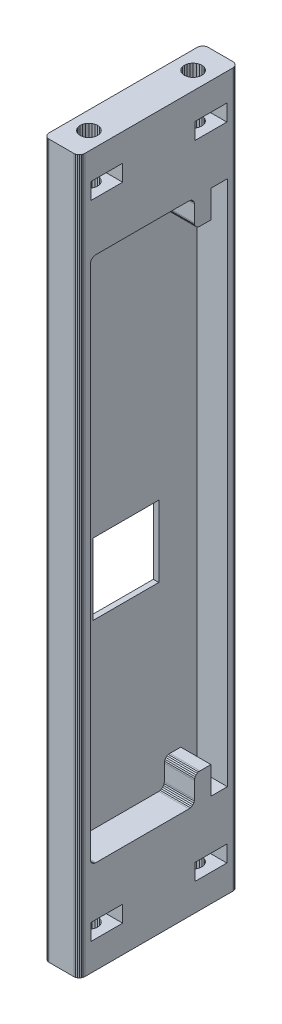
SolidWorks part; units mm, degrees
ref_plane "Front Plane" through (0, 0, 0) normal (0, 0, 1) x (1, 0, 0)
ref_plane "Top Plane" through (0, 0, 0) normal (0, 1, 0) x (1, 0, 0)
ref_plane "Right Plane" through (0, 0, 0) normal (1, 0, 0) x (0, 0, -1)
ref_plane "Plane1" through (0, 130, 0) normal (0, 1, 0) x (1, 0, 0)
sketch "Sketch1" plane through (0, 130, 0) normal (0, 1, 0) x (1, 0, 0)
  line L0 (3.2159, -23.2588) -> (3.25, -23)
  line L1 (3.25, -23) -> (3.25, 4)
  line L2 (3.25, 4) -> (3.2159, 4.2588)
  line L3 (3.2159, 4.2588) -> (3.116, 4.5)
  line L4 (3.116, 4.5) -> (2.9571, 4.7071)
  line L5 (2.9571, 4.7071) -> (2.75, 4.866)
  line L6 (2.75, 4.866) -> (2.5088, 4.9659)
  line L7 (2.5088, 4.9659) -> (2.25, 5)
  line L8 (2.25, 5) -> (-2.25, 5)
  line L9 (-2.25, 5) -> (-2.5088, 4.9659)
  line L10 (-2.5088, 4.9659) -> (-2.75, 4.866)
  line L11 (-2.75, 4.866) -> (-2.9571, 4.7071)
  line L12 (-2.9571, 4.7071) -> (-3.116, 4.5)
  line L13 (-3.116, 4.5) -> (-3.2159, 4.2588)
  line L14 (-3.2159, 4.2588) -> (-3.25, 4)
  line L15 (-3.25, 4) -> (-3.25, -23)
  line L16 (-3.25, -23) -> (-3.2159, -23.2588)
  line L17 (-3.2159, -23.2588) -> (-3.116, -23.5)
  line L18 (-3.116, -23.5) -> (-2.9571, -23.7071)
  line L19 (-2.9571, -23.7071) -> (-2.75, -23.866)
  line L20 (-2.75, -23.866) -> (-2.5088, -23.9659)
  line L21 (-2.5088, -23.9659) -> (-2.25, -24)
  line L22 (-2.25, -24) -> (2.25, -24)
  line L23 (2.25, -24) -> (2.5088, -23.9659)
  line L24 (2.5088, -23.9659) -> (2.75, -23.866)
  line L25 (2.75, -23.866) -> (2.9571, -23.7071)
  line L26 (2.9571, -23.7071) -> (3.116, -23.5)
  line L27 (3.116, -23.5) -> (3.2159, -23.2588)
extrude "Boss-Extrude1" add sketch "Sketch1" against normal blind 130
sketch "Sketch2" plane through (-3.25, 0, 0) normal (-1, 0, 0) x (0, 0, 1)
  line L0 (16.1, 5) -> (21.9, 5)
  line L1 (21.9, 5) -> (21.9, 8)
  line L2 (21.9, 8) -> (16.1, 8)
  line L3 (16.1, 8) -> (16.1, 5)
extrude "Cut-Extrude1" cut sketch "Sketch2" against normal through all
sketch "Sketch3" plane through (0, 0, 0) normal (0, -1, 0) x (1, 0, 0)
  line L0 (1.5455, 18.5859) -> (1.6, 19)
  line L1 (1.6, 19) -> (1.5455, 19.4141)
  line L2 (1.5455, 19.4141) -> (1.3856, 19.8)
  line L3 (1.3856, 19.8) -> (1.1314, 20.1314)
  line L4 (1.1314, 20.1314) -> (0.8, 20.3856)
  line L5 (0.8, 20.3856) -> (0.4141, 20.5455)
  line L6 (0.4141, 20.5455) -> (0, 20.6)
  line L7 (0, 20.6) -> (-0.4141, 20.5455)
  line L8 (-0.4141, 20.5455) -> (-0.8, 20.3856)
  line L9 (-0.8, 20.3856) -> (-1.1314, 20.1314)
  line L10 (-1.1314, 20.1314) -> (-1.3856, 19.8)
  line L11 (-1.3856, 19.8) -> (-1.5455, 19.4141)
  line L12 (-1.5455, 19.4141) -> (-1.6, 19)
  line L13 (-1.6, 19) -> (-1.5455, 18.5859)
  line L14 (-1.5455, 18.5859) -> (-1.3856, 18.2)
  line L15 (-1.3856, 18.2) -> (-1.1314, 17.8686)
  line L16 (-1.1314, 17.8686) -> (-0.8, 17.6144)
  line L17 (-0.8, 17.6144) -> (-0.4141, 17.4545)
  line L18 (-0.4141, 17.4545) -> (0, 17.4)
  line L19 (0, 17.4) -> (0.4141, 17.4545)
  line L20 (0.4141, 17.4545) -> (0.8, 17.6144)
  line L21 (0.8, 17.6144) -> (1.1314, 17.8686)
  line L22 (1.1314, 17.8686) -> (1.3856, 18.2)
  line L23 (1.3856, 18.2) -> (1.5455, 18.5859)
extrude "Cut-Extrude2" cut sketch "Sketch3" against normal up to next
sketch "Sketch4" plane through (-3.25, 0, 0) normal (-1, 0, 0) x (0, 0, 1)
  line L0 (2.9, 125) -> (-2.9, 125)
  line L1 (-2.9, 125) -> (-2.9, 122)
  line L2 (-2.9, 122) -> (2.9, 122)
  line L3 (2.9, 122) -> (2.9, 125)
extrude "Cut-Extrude3" cut sketch "Sketch4" against normal through all
sketch "Sketch5" plane through (-3.25, 0, 0) normal (-1, 0, 0) x (0, 0, 1)
  line L0 (-2.9, 8) -> (-2.9, 5)
  line L1 (-2.9, 5) -> (2.9, 5)
  line L2 (2.9, 5) -> (2.9, 8)
  line L3 (2.9, 8) -> (-2.9, 8)
extrude "Cut-Extrude4" cut sketch "Sketch5" against normal through all
sketch "Sketch6" plane through (-3.25, 0, 0) normal (-1, 0, 0) x (0, 0, 1)
  line L0 (21.9, 122) -> (21.9, 125)
  line L1 (21.9, 125) -> (16.1, 125)
  line L2 (16.1, 125) -> (16.1, 122)
  line L3 (16.1, 122) -> (21.9, 122)
extrude "Cut-Extrude5" cut sketch "Sketch6" against normal through all
sketch "Sketch7" plane through (0, 130, 0) normal (0, 1, 0) x (-1, 0, 0)
  line L0 (-1.3856, 0.8) -> (-1.5455, 0.4141)
  line L1 (-1.5455, 0.4141) -> (-1.6, 0)
  line L2 (-1.6, 0) -> (-1.5455, -0.4141)
  line L3 (-1.5455, -0.4141) -> (-1.3856, -0.8)
  line L4 (-1.3856, -0.8) -> (-1.1314, -1.1314)
  line L5 (-1.1314, -1.1314) -> (-0.8, -1.3856)
  line L6 (-0.8, -1.3856) -> (-0.4141, -1.5455)
  line L7 (-0.4141, -1.5455) -> (0, -1.6)
  line L8 (0, -1.6) -> (0.4141, -1.5455)
  line L9 (0.4141, -1.5455) -> (0.8, -1.3856)
  line L10 (0.8, -1.3856) -> (1.1314, -1.1314)
  line L11 (1.1314, -1.1314) -> (1.3856, -0.8)
  line L12 (1.3856, -0.8) -> (1.5455, -0.4141)
  line L13 (1.5455, -0.4141) -> (1.6, 0)
  line L14 (1.6, 0) -> (1.5455, 0.4141)
  line L15 (1.5455, 0.4141) -> (1.3856, 0.8)
  line L16 (1.3856, 0.8) -> (1.1314, 1.1314)
  line L17 (1.1314, 1.1314) -> (0.8, 1.3856)
  line L18 (0.8, 1.3856) -> (0.4141, 1.5455)
  line L19 (0.4141, 1.5455) -> (0, 1.6)
  line L20 (0, 1.6) -> (-0.4141, 1.5455)
  line L21 (-0.4141, 1.5455) -> (-0.8, 1.3856)
  line L22 (-0.8, 1.3856) -> (-1.1314, 1.1314)
  line L23 (-1.1314, 1.1314) -> (-1.3856, 0.8)
extrude "Cut-Extrude6" cut sketch "Sketch7" against normal up to next
sketch "Sketch8" plane through (0, 130, 0) normal (0, 1, 0) x (-1, 0, 0)
  line L0 (-1.6, 19) -> (-1.5455, 18.5859)
  line L1 (-1.5455, 18.5859) -> (-1.3856, 18.2)
  line L2 (-1.3856, 18.2) -> (-1.1314, 17.8686)
  line L3 (-1.1314, 17.8686) -> (-0.8, 17.6144)
  line L4 (-0.8, 17.6144) -> (-0.4141, 17.4545)
  line L5 (-0.4141, 17.4545) -> (0, 17.4)
  line L6 (0, 17.4) -> (0.4141, 17.4545)
  line L7 (0.4141, 17.4545) -> (0.8, 17.6144)
  line L8 (0.8, 17.6144) -> (1.1314, 17.8686)
  line L9 (1.1314, 17.8686) -> (1.3856, 18.2)
  line L10 (1.3856, 18.2) -> (1.5455, 18.5859)
  line L11 (1.5455, 18.5859) -> (1.6, 19)
  line L12 (1.6, 19) -> (1.5455, 19.4141)
  line L13 (1.5455, 19.4141) -> (1.3856, 19.8)
  line L14 (1.3856, 19.8) -> (1.1314, 20.1314)
  line L15 (1.1314, 20.1314) -> (0.8, 20.3856)
  line L16 (0.8, 20.3856) -> (0.4141, 20.5455)
  line L17 (0.4141, 20.5455) -> (0, 20.6)
  line L18 (0, 20.6) -> (-0.4141, 20.5455)
  line L19 (-0.4141, 20.5455) -> (-0.8, 20.3856)
  line L20 (-0.8, 20.3856) -> (-1.1314, 20.1314)
  line L21 (-1.1314, 20.1314) -> (-1.3856, 19.8)
  line L22 (-1.3856, 19.8) -> (-1.5455, 19.4141)
  line L23 (-1.5455, 19.4141) -> (-1.6, 19)
extrude "Cut-Extrude7" cut sketch "Sketch8" against normal up to next
sketch "Sketch9" plane through (3.25, 0, 0) normal (1, 0, 0) x (0, 0, -1)
  line L0 (-2.5, 108.134) -> (-2.7071, 108.2929)
  line L1 (-2.7071, 108.2929) -> (-2.866, 108.5)
  line L2 (-2.866, 108.5) -> (-2.9659, 108.7412)
  line L3 (-2.9659, 108.7412) -> (-3, 109)
  line L4 (-3, 109) -> (-3, 112)
  line L5 (-3, 112) -> (-3.0341, 112.2588)
  line L6 (-3.0341, 112.2588) -> (-3.134, 112.5)
  line L7 (-3.134, 112.5) -> (-3.2929, 112.7071)
  line L8 (-3.2929, 112.7071) -> (-3.5, 112.866)
  line L9 (-3.5, 112.866) -> (-3.7412, 112.9659)
  line L10 (-3.7412, 112.9659) -> (-4, 113)
  line L11 (-4, 113) -> (-21, 113)
  line L12 (-21, 113) -> (-21.2588, 112.9659)
  line L13 (-21.2588, 112.9659) -> (-21.5, 112.866)
  line L14 (-21.5, 112.866) -> (-21.7071, 112.7071)
  line L15 (-21.7071, 112.7071) -> (-21.866, 112.5)
  line L16 (-21.866, 112.5) -> (-21.9659, 112.2588)
  line L17 (-21.9659, 112.2588) -> (-22, 112)
  line L18 (-22, 112) -> (-22, 18)
  line L19 (-22, 18) -> (-21.9659, 17.7412)
  line L20 (-21.9659, 17.7412) -> (-21.866, 17.5)
  line L21 (-21.866, 17.5) -> (-21.7071, 17.2929)
  line L22 (-21.7071, 17.2929) -> (-21.5, 17.134)
  line L23 (-21.5, 17.134) -> (-21.2588, 17.0341)
  line L24 (-21.2588, 17.0341) -> (-21, 17)
  line L25 (-21, 17) -> (-4, 17)
  line L26 (-4, 17) -> (-3.7412, 17.0341)
  line L27 (-3.7412, 17.0341) -> (-3.5, 17.134)
  line L28 (-3.5, 17.134) -> (-3.2929, 17.2929)
  line L29 (-3.2929, 17.2929) -> (-3.134, 17.5)
  line L30 (-3.134, 17.5) -> (-3.0341, 17.7412)
  line L31 (-3.0341, 17.7412) -> (-3, 18)
  line L32 (-3, 18) -> (-3, 21)
  line L33 (-3, 21) -> (-2.9659, 21.2588)
  line L34 (-2.9659, 21.2588) -> (-2.866, 21.5)
  line L35 (-2.866, 21.5) -> (-2.7071, 21.7071)
  line L36 (-2.7071, 21.7071) -> (-2.5, 21.866)
  line L37 (-2.5, 21.866) -> (-2.2588, 21.9659)
  line L38 (-2.2588, 21.9659) -> (-2, 22)
  line L39 (-2, 22) -> (0, 22)
  line L40 (0, 22) -> (0, 17)
  line L41 (0, 17) -> (3, 17)
  line L42 (3, 17) -> (3, 113)
  line L43 (3, 113) -> (0, 113)
  line L44 (0, 113) -> (0, 108)
  line L45 (0, 108) -> (-2, 108)
  line L46 (-2, 108) -> (-2.2588, 108.0341)
  line L47 (-2.2588, 108.0341) -> (-2.5, 108.134)
extrude "Cut-Extrude8" cut sketch "Sketch9" against normal blind 5.5
sketch "Sketch10" plane through (-3.25, 0, 0) normal (-1, 0, 0) x (0, 0, 1)
  line L0 (4, 50) -> (16, 50)
  line L1 (16, 50) -> (16, 63)
  line L2 (16, 63) -> (4, 63)
  line L3 (4, 63) -> (4, 50)
extrude "Cut-Extrude9" cut sketch "Sketch10" against normal through all
sketch "Sketch11" plane through (0, 0, 0) normal (0, -1, 0) x (1, 0, 0)
  line L0 (0.8, 1.3856) -> (0.4141, 1.5455)
  line L1 (0.4141, 1.5455) -> (0, 1.6)
  line L2 (0, 1.6) -> (-0.4141, 1.5455)
  line L3 (-0.4141, 1.5455) -> (-0.8, 1.3856)
  line L4 (-0.8, 1.3856) -> (-1.1314, 1.1314)
  line L5 (-1.1314, 1.1314) -> (-1.3856, 0.8)
  line L6 (-1.3856, 0.8) -> (-1.5455, 0.4141)
  line L7 (-1.5455, 0.4141) -> (-1.6, 0)
  line L8 (-1.6, 0) -> (-1.5455, -0.4141)
  line L9 (-1.5455, -0.4141) -> (-1.3856, -0.8)
  line L10 (-1.3856, -0.8) -> (-1.1314, -1.1314)
  line L11 (-1.1314, -1.1314) -> (-0.8, -1.3856)
  line L12 (-0.8, -1.3856) -> (-0.4141, -1.5455)
  line L13 (-0.4141, -1.5455) -> (0, -1.6)
  line L14 (0, -1.6) -> (0.4141, -1.5455)
  line L15 (0.4141, -1.5455) -> (0.8, -1.3856)
  line L16 (0.8, -1.3856) -> (1.1314, -1.1314)
  line L17 (1.1314, -1.1314) -> (1.3856, -0.8)
  line L18 (1.3856, -0.8) -> (1.5455, -0.4141)
  line L19 (1.5455, -0.4141) -> (1.6, 0)
  line L20 (1.6, 0) -> (1.5455, 0.4141)
  line L21 (1.5455, 0.4141) -> (1.3856, 0.8)
  line L22 (1.3856, 0.8) -> (1.1314, 1.1314)
  line L23 (1.1314, 1.1314) -> (0.8, 1.3856)
extrude "Cut-Extrude10" cut sketch "Sketch11" against normal up to next
sketch "Sketch12" plane through (0, 122, 0) normal (0, 1, 0) x (-1, 0, 0)
  line L0 (1.5455, -0.4141) -> (1.6, 0)
  line L1 (1.6, 0) -> (1.5455, 0.4141)
  line L2 (1.5455, 0.4141) -> (1.3856, 0.8)
  line L3 (1.3856, 0.8) -> (1.1314, 1.1314)
  line L4 (1.1314, 1.1314) -> (0.8, 1.3856)
  line L5 (0.8, 1.3856) -> (0.4141, 1.5455)
  line L6 (0.4141, 1.5455) -> (0, 1.6)
  line L7 (0, 1.6) -> (-0.4141, 1.5455)
  line L8 (-0.4141, 1.5455) -> (-0.8, 1.3856)
  line L9 (-0.8, 1.3856) -> (-1.1314, 1.1314)
  line L10 (-1.1314, 1.1314) -> (-1.3856, 0.8)
  line L11 (-1.3856, 0.8) -> (-1.5455, 0.4141)
  line L12 (-1.5455, 0.4141) -> (-1.6, 0)
  line L13 (-1.6, 0) -> (-1.5455, -0.4141)
  line L14 (-1.5455, -0.4141) -> (-1.3856, -0.8)
  line L15 (-1.3856, -0.8) -> (-1.1314, -1.1314)
  line L16 (-1.1314, -1.1314) -> (-0.8, -1.3856)
  line L17 (-0.8, -1.3856) -> (-0.4141, -1.5455)
  line L18 (-0.4141, -1.5455) -> (0, -1.6)
  line L19 (0, -1.6) -> (0.4141, -1.5455)
  line L20 (0.4141, -1.5455) -> (0.8, -1.3856)
  line L21 (0.8, -1.3856) -> (1.1314, -1.1314)
  line L22 (1.1314, -1.1314) -> (1.3856, -0.8)
  line L23 (1.3856, -0.8) -> (1.5455, -0.4141)
extrude "Cut-Extrude11" cut sketch "Sketch12" against normal blind 7
sketch "Sketch13" plane through (0, 122, 0) normal (0, 1, 0) x (-1, 0, 0)
  line L0 (1.5455, 18.5859) -> (1.6, 19)
  line L1 (1.6, 19) -> (1.5455, 19.4141)
  line L2 (1.5455, 19.4141) -> (1.3856, 19.8)
  line L3 (1.3856, 19.8) -> (1.1314, 20.1314)
  line L4 (1.1314, 20.1314) -> (0.8, 20.3856)
  line L5 (0.8, 20.3856) -> (0.4141, 20.5455)
  line L6 (0.4141, 20.5455) -> (0, 20.6)
  line L7 (0, 20.6) -> (-0.4141, 20.5455)
  line L8 (-0.4141, 20.5455) -> (-0.8, 20.3856)
  line L9 (-0.8, 20.3856) -> (-1.1314, 20.1314)
  line L10 (-1.1314, 20.1314) -> (-1.3856, 19.8)
  line L11 (-1.3856, 19.8) -> (-1.5455, 19.4141)
  line L12 (-1.5455, 19.4141) -> (-1.6, 19)
  line L13 (-1.6, 19) -> (-1.5455, 18.5859)
  line L14 (-1.5455, 18.5859) -> (-1.3856, 18.2)
  line L15 (-1.3856, 18.2) -> (-1.1314, 17.8686)
  line L16 (-1.1314, 17.8686) -> (-0.8, 17.6144)
  line L17 (-0.8, 17.6144) -> (-0.4141, 17.4545)
  line L18 (-0.4141, 17.4545) -> (0, 17.4)
  line L19 (0, 17.4) -> (0.4141, 17.4545)
  line L20 (0.4141, 17.4545) -> (0.8, 17.6144)
  line L21 (0.8, 17.6144) -> (1.1314, 17.8686)
  line L22 (1.1314, 17.8686) -> (1.3856, 18.2)
  line L23 (1.3856, 18.2) -> (1.5455, 18.5859)
extrude "Cut-Extrude12" cut sketch "Sketch13" against normal blind 7
sketch "Sketch14" plane through (0, 8, 0) normal (0, -1, 0) x (1, 0, 0)
  line L0 (-0.4141, -1.5455) -> (0, -1.6)
  line L1 (0, -1.6) -> (0.4141, -1.5455)
  line L2 (0.4141, -1.5455) -> (0.8, -1.3856)
  line L3 (0.8, -1.3856) -> (1.1314, -1.1314)
  line L4 (1.1314, -1.1314) -> (1.3856, -0.8)
  line L5 (1.3856, -0.8) -> (1.5455, -0.4141)
  line L6 (1.5455, -0.4141) -> (1.6, 0)
  line L7 (1.6, 0) -> (1.5455, 0.4141)
  line L8 (1.5455, 0.4141) -> (1.3856, 0.8)
  line L9 (1.3856, 0.8) -> (1.1314, 1.1314)
  line L10 (1.1314, 1.1314) -> (0.8, 1.3856)
  line L11 (0.8, 1.3856) -> (0.4141, 1.5455)
  line L12 (0.4141, 1.5455) -> (0, 1.6)
  line L13 (0, 1.6) -> (-0.4141, 1.5455)
  line L14 (-0.4141, 1.5455) -> (-0.8, 1.3856)
  line L15 (-0.8, 1.3856) -> (-1.1314, 1.1314)
  line L16 (-1.1314, 1.1314) -> (-1.3856, 0.8)
  line L17 (-1.3856, 0.8) -> (-1.5455, 0.4141)
  line L18 (-1.5455, 0.4141) -> (-1.6, 0)
  line L19 (-1.6, 0) -> (-1.5455, -0.4141)
  line L20 (-1.5455, -0.4141) -> (-1.3856, -0.8)
  line L21 (-1.3856, -0.8) -> (-1.1314, -1.1314)
  line L22 (-1.1314, -1.1314) -> (-0.8, -1.3856)
  line L23 (-0.8, -1.3856) -> (-0.4141, -1.5455)
extrude "Cut-Extrude13" cut sketch "Sketch14" against normal blind 7
sketch "Sketch15" plane through (0, 8, 0) normal (0, -1, 0) x (1, 0, 0)
  line L0 (0, 17.4) -> (0.4141, 17.4545)
  line L1 (0.4141, 17.4545) -> (0.8, 17.6144)
  line L2 (0.8, 17.6144) -> (1.1314, 17.8686)
  line L3 (1.1314, 17.8686) -> (1.3856, 18.2)
  line L4 (1.3856, 18.2) -> (1.5455, 18.5859)
  line L5 (1.5455, 18.5859) -> (1.6, 19)
  line L6 (1.6, 19) -> (1.5455, 19.4141)
  line L7 (1.5455, 19.4141) -> (1.3856, 19.8)
  line L8 (1.3856, 19.8) -> (1.1314, 20.1314)
  line L9 (1.1314, 20.1314) -> (0.8, 20.3856)
  line L10 (0.8, 20.3856) -> (0.4141, 20.5455)
  line L11 (0.4141, 20.5455) -> (0, 20.6)
  line L12 (0, 20.6) -> (-0.4141, 20.5455)
  line L13 (-0.4141, 20.5455) -> (-0.8, 20.3856)
  line L14 (-0.8, 20.3856) -> (-1.1314, 20.1314)
  line L15 (-1.1314, 20.1314) -> (-1.3856, 19.8)
  line L16 (-1.3856, 19.8) -> (-1.5455, 19.4141)
  line L17 (-1.5455, 19.4141) -> (-1.6, 19)
  line L18 (-1.6, 19) -> (-1.5455, 18.5859)
  line L19 (-1.5455, 18.5859) -> (-1.3856, 18.2)
  line L20 (-1.3856, 18.2) -> (-1.1314, 17.8686)
  line L21 (-1.1314, 17.8686) -> (-0.8, 17.6144)
  line L22 (-0.8, 17.6144) -> (-0.4141, 17.4545)
  line L23 (-0.4141, 17.4545) -> (0, 17.4)
extrude "Cut-Extrude14" cut sketch "Sketch15" against normal blind 7
